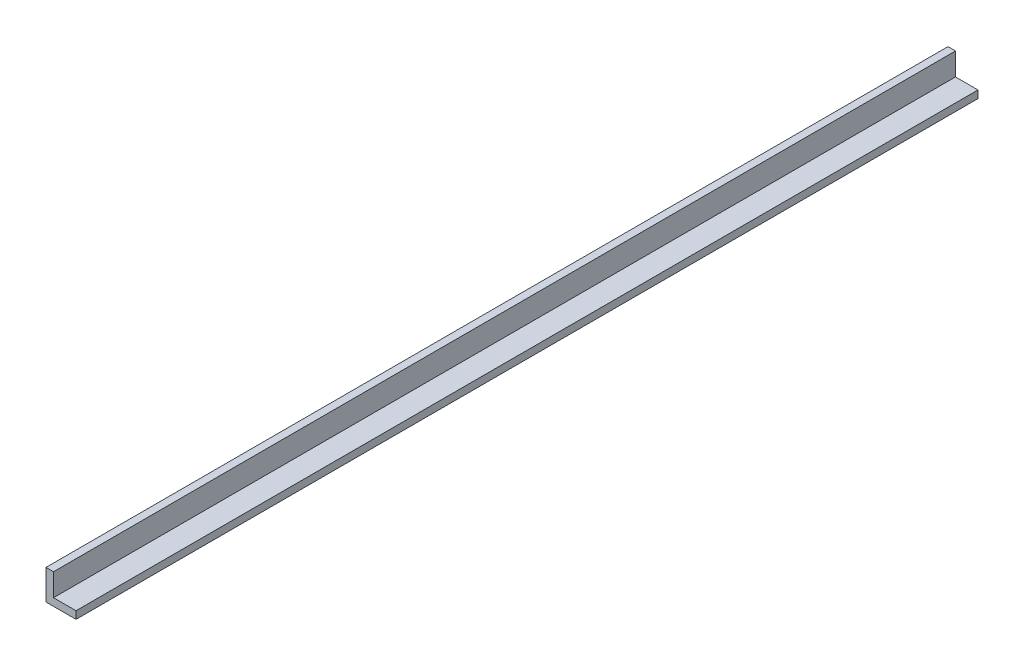
SolidWorks part; units mm, degrees
material "ASTM A36 Acero"
ref_plane "Alzado" through (0, 0, 0) normal (0, 0, 1) x (1, 0, 0)
ref_plane "Planta" through (0, 0, 0) normal (0, 1, 0) x (1, 0, 0)
ref_plane "Vista lateral" through (0, 0, 0) normal (1, 0, 0) x (0, 0, -1)
sketch "Croquis1" plane through (0, 0, 0) normal (0, 0, 1) x (1, 0, 0)
  line L0 (0, 203) -> (0, 0)
  line L1 (0, 0) -> (203, 0)
  line L2 (203, 0) -> (203, 50.8)
  line L3 (203, 50.8) -> (50.8, 50.8)
  line L4 (50.8, 50.8) -> (50.8, 203)
  line L5 (50.8, 203) -> (0, 203)
  dimension "D1" = 50.8
  dimension "D2" = 203
extrude "Saliente-Extruir1" add sketch "Croquis1" against normal blind 6100
